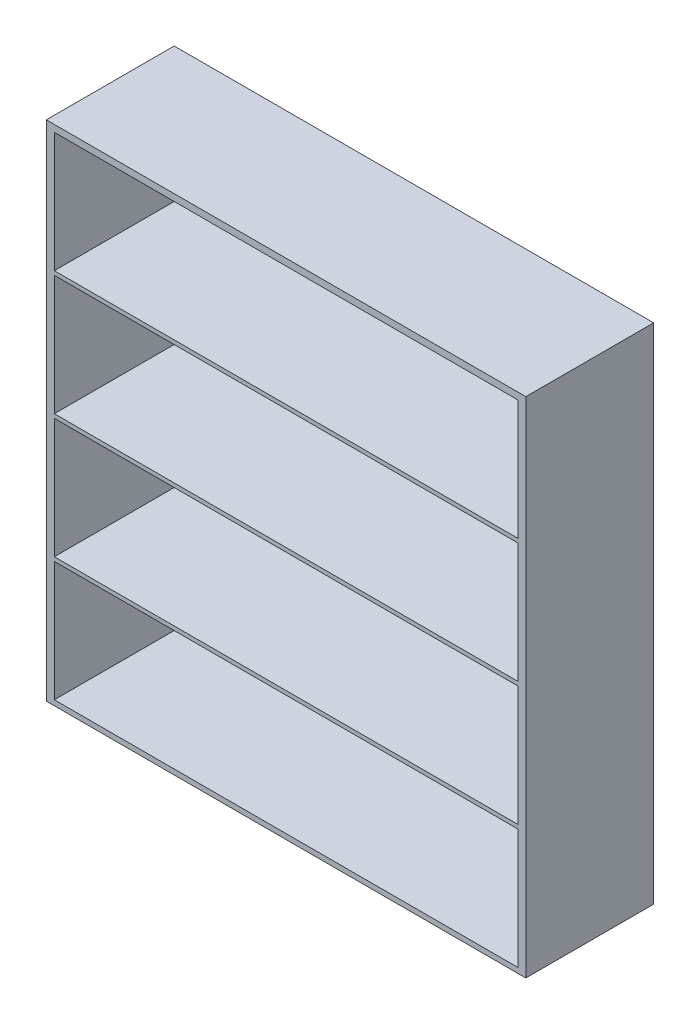
SolidWorks part; units mm, degrees
ref_plane "Front Plane" through (0, 0, 0) normal (0, 0, 1) x (1, 0, 0)
ref_plane "Top Plane" through (0, 0, 0) normal (0, 1, 0) x (1, 0, 0)
ref_plane "Right Plane" through (0, 0, 0) normal (1, 0, 0) x (0, 0, -1)
sketch "Sketch1" plane through (0, 0, 0) normal (0, 0, 1) x (1, 0, 0)
  line L1 (0, 0) -> (60, 0)
  line L2 (0, 0) -> (0, 63)
  line L3 (0, 63) -> (60, 63)
  line L4 (60, 0) -> (60, 63)
  dimension "D1" = 63
  dimension "D2" = 60
extrude "Boss-Extrude1" add sketch "Sketch1" along normal blind 16
sketch "Sketch3" plane through (0, 0, 16) normal (0, 0, 1) x (1, 0, 0)
  line L0 (0, 63) -> (0, 0) construction
  line L1 (1, 15.65) -> (59, 15.65)
  line L2 (1, 15.65) -> (1, 0.65)
  line L3 (1, 0.65) -> (59, 0.65)
  line L4 (59, 15.65) -> (59, 0.65)
  line L5 (0, 0) -> (60, 0) construction
  line L7 (60, 0) -> (60, 63) construction
  line L8 (1, 31.15) -> (59, 31.15)
  line L9 (1, 31.15) -> (1, 16.15)
  line L10 (1, 16.15) -> (59, 16.15)
  line L11 (59, 31.15) -> (59, 16.15)
  line L12 (1, 46.65) -> (59, 46.65)
  line L13 (1, 46.65) -> (1, 31.65)
  line L14 (1, 31.65) -> (59, 31.65)
  line L15 (59, 46.65) -> (59, 31.65)
  line L16 (1, 62.15) -> (59, 62.15)
  line L17 (1, 62.15) -> (1, 47.15)
  line L18 (1, 47.15) -> (59, 47.15)
  line L19 (59, 62.15) -> (59, 47.15)
  dimension "D1" = 15
  dimension "D2" = 1
  dimension "D3" = 1
  dimension "D4" = 0.65
  dimension "D5" = 4
extrude "Cut-Extrude1" cut sketch "Sketch3" against normal blind 15
